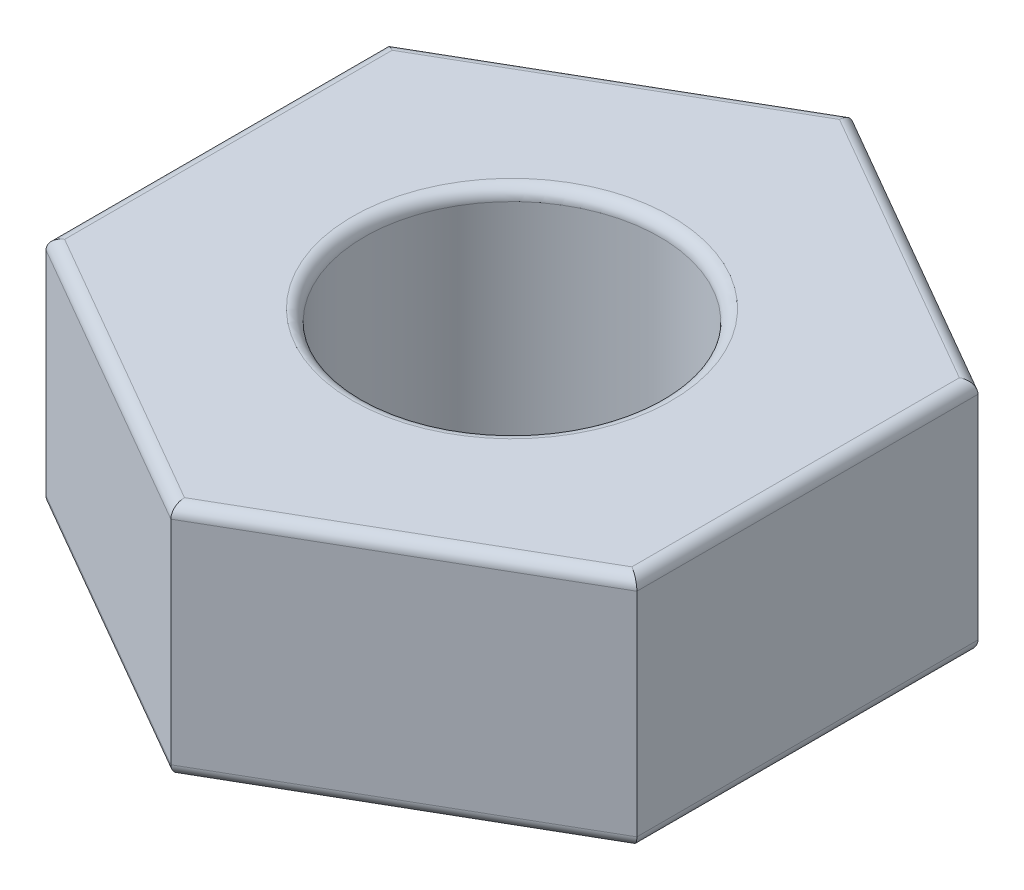
SolidWorks part; units mm, degrees
ref_plane "Front Plane" through (0, 0, 0) normal (0, 0, 1) x (1, 0, 0)
ref_plane "Top Plane" through (0, 0, 0) normal (0, 1, 0) x (1, 0, 0)
ref_plane "Right Plane" through (0, 0, 0) normal (1, 0, 0) x (0, 0, -1)
sketch "Sketch1" plane through (0, 0, 0) normal (0, 1, 0) x (1, 0, 0)
  line L1 (0, 2.8868) -> (-2.5, 1.4434)
  line L2 (-2.5, 1.4434) -> (-2.5, -1.4434)
  line L3 (-2.5, -1.4434) -> (0, -2.8868)
  line L4 (0, -2.8868) -> (2.5, -1.4434)
  line L5 (2.5, -1.4434) -> (2.5, 1.4434)
  line L6 (2.5, 1.4434) -> (0, 2.8868)
  circle A0 centre (0, 0) radius 1.25
  circle A2 centre (0, 0) radius 2.5 construction
  dimension "D1" = 2.5
  dimension "D3" = 5
extrude "Boss-Extrude1" add sketch "Sketch1" along normal mid plane 2
fillet "Fillet1" radius 0.1 14 edges at (0, -1, 1.25) (-1.25, -1, -2.1651) (-2.5, -1, 0) (-1.25, -1, 2.1651) (1.25, -1, 2.1651) (2.5, -1, 0) (1.25, -1, -2.1651) (0, 1, 1.25) (2.5, 1, 0) (1.25, 1, 2.1651) (-1.25, 1, 2.1651) (-2.5, 1, 0) (-1.25, 1, -2.1651) (1.25, 1, -2.1651)
